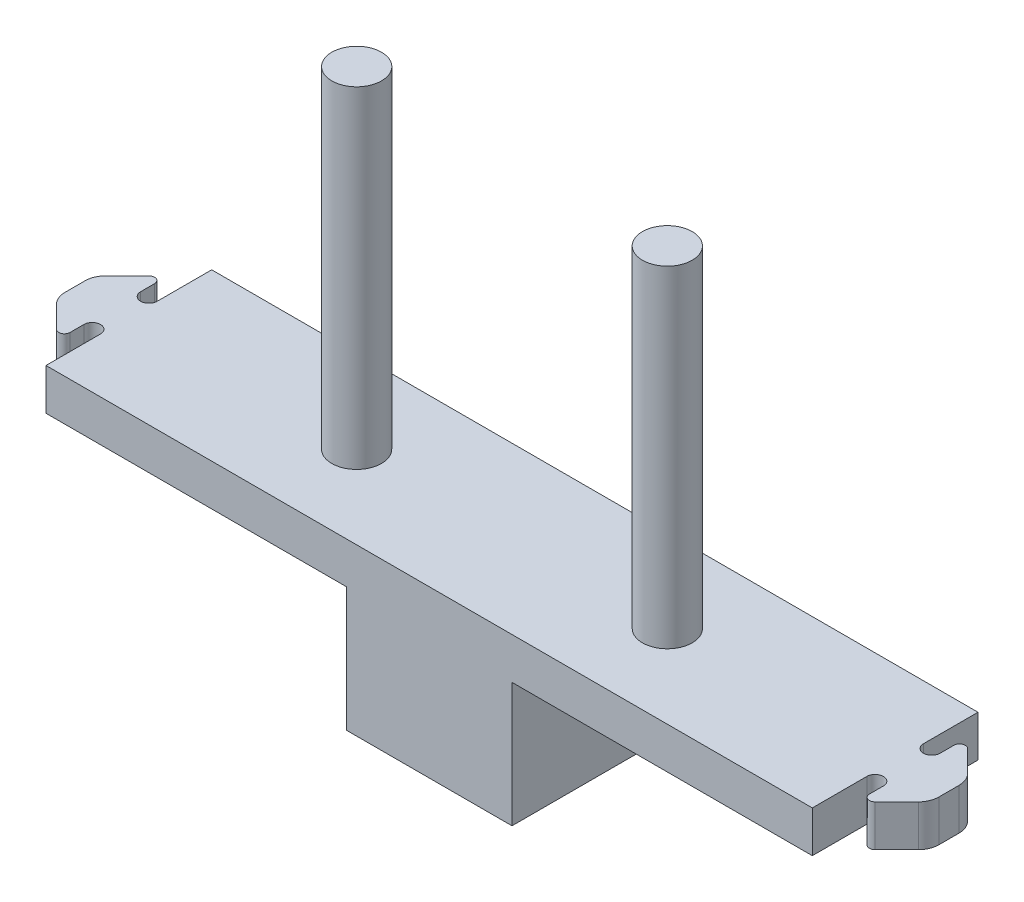
SolidWorks part; units mm, degrees
ref_plane "Front Plane" through (0, 0, 0) normal (0, 0, 1) x (1, 0, 0)
ref_plane "Top Plane" through (0, 0, 0) normal (0, 1, 0) x (1, 0, 0)
ref_plane "Right Plane" through (0, 0, 0) normal (1, 0, 0) x (0, 0, -1)
sketch "Sketch1" plane through (0, 0, 0) normal (0, 1, 0) x (1, 0, 0)
  line L0 (12.1572, -15.7678) -> (7.8138, -15.7678)
  line L1 (0, 0) -> (-117.475, 0)
  line L2 (0, 0) -> (0, -25.4)
  line L3 (0, -25.4) -> (-117.475, -25.4)
  line L4 (-117.475, 0) -> (-117.475, -25.4)
  line L13 (7.8138, -13.2278) -> (5.6802, -13.2278)
  line L14 (5.0695, -11.7535) -> (8.3922, -8.4308)
  line L15 (10.6437, -7.5166) -> (12.1572, -7.5166)
  line L16 (12.1572, -7.5166) -> (12.1572, -15.7678)
  arc A0 (7.8138, -15.7678) -> (7.8138, -13.2278) centre (7.8138, -14.4978) ccw
  arc A1 (5.6802, -13.2278) -> (5.0695, -11.7535) centre (5.6802, -12.3642) cw
  arc A2 (8.3922, -8.4308) -> (10.6437, -7.5166) centre (10.6216, -10.6915) cw
  point P18 (11.4004, -7.5166)
  dimension "D5" = 6.477
  dimension "D7" = 1.27
  dimension "D8" = 0.8636
  dimension "D9" = 3.175
  dimension "D1" = 117.475
  dimension "D2" = 25.4
  dimension "D3" = 4.3434
  dimension "D4" = 8.2512
  dimension "D6" = 45
  dimension "D10" = 2.54
  dimension "D11" = 3.4036
  dimension "D12" = 5.0763
  dimension "D13" = 1.5356
  dimension "D14" = 4.3434
  dimension "D15" = 4.0143
extrude "Boss-Extrude1" add sketch "Sketch1" along normal blind 6.35
sketch "Sketch3" plane through (0, 6.35, 0) normal (0, 1, 0) x (1, 0, 0)
  line L0 (0, 0) -> (-117.475, 0) construction
  line L1 (-114.3, 0) -> (-3.175, 0)
  line L2 (-114.3, 0) -> (-114.3, -25.4)
  line L3 (-114.3, -25.4) -> (-3.175, -25.4)
  line L4 (-3.175, 0) -> (-3.175, -25.4)
  line L5 (0, -25.4) -> (-117.475, -25.4) construction
  line L6 (0, -25.4) -> (-117.475, -25.4) construction
  circle A0 centre (-34.925, -12.7) radius 3.81
  circle A1 centre (-82.55, -12.7) radius 3.81
  point P8 (-58.7375, 0)
  point P11 (-58.7375, -25.4)
  dimension "D3" = 12.7
  dimension "D7" = 7.62
  dimension "D8" = 7.62
  dimension "D1" = 111.125
  dimension "D2" = 0
  dimension "D4" = 31.75
  dimension "D5" = 12.7
  dimension "D6" = 31.75
extrude "Boss-Extrude2" add sketch "Sketch3" along normal blind 50.8 contours A0 | A1
sketch "Sketch4" plane through (0, 6.35, 0) normal (0, 1, 0) x (1, 0, 0)
  circle A0 centre (-82.55, -12.7) radius 12.7
  circle A1 centre (-34.925, -12.7) radius 12.7
extrude "Boss-Extrude3" [suppressed] add sketch "Sketch4" along normal blind 50.8
ref_plane "Plane1" through (-58.7375, 0, 0) normal (-1, 0, 0) x (0, 0, 1)
sketch "Sketch10" plane through (0, 6.35, 0) normal (0, 1, 0) x (1, 0, 0)
  line L5 (0, -12.7) -> (0, -8.3566)
  line L6 (2.54, -8.3566) -> (2.54, -6.223)
  line L7 (4.0143, -5.6123) -> (7.337, -8.935)
  line L8 (8.2512, -11.1865) -> (8.2512, -12.7)
  line L9 (8.2512, -12.7) -> (0, -12.7)
  line L10 (-58.7375, 3.4925) -> (-58.7375, -3.4925) construction
  line L11 (0, 0) -> (0, -25.4) construction
  line L12 (-117.475, -12.7) -> (-117.475, -8.3566)
  line L13 (-120.015, -8.3566) -> (-120.015, -6.223)
  line L14 (-121.4893, -5.6123) -> (-124.812, -8.935)
  line L15 (-125.7262, -11.1865) -> (-125.7262, -12.7)
  line L16 (-125.7262, -12.7) -> (-117.475, -12.7)
  arc A3 (0, -8.3566) -> (2.54, -8.3566) centre (1.27, -8.3566) ccw
  arc A4 (2.54, -6.223) -> (4.0143, -5.6123) centre (3.4036, -6.223) cw
  arc A5 (7.337, -8.935) -> (8.2512, -11.1865) centre (5.0763, -11.1644) cw
  arc A6 (-117.475, -8.3566) -> (-120.015, -8.3566) centre (-118.745, -8.3566) cw
  arc A7 (-120.015, -6.223) -> (-121.4893, -5.6123) centre (-120.8786, -6.223) ccw
  arc A8 (-124.812, -8.935) -> (-125.7262, -11.1865) centre (-122.5513, -11.1644) ccw
  point P2 (0, -12.7)
extrude "Boss-Extrude7" add sketch "Sketch10" against normal blind 6.35
mirror "Mirror1" about plane through (8.2512, 0, 12.7) normal (0, 0, 1) of "Boss-Extrude7"
sketch "Sketch12" plane through (0, 0, 0) normal (0, -1, 0) x (-1, 0, 0)
  line L0 (0, -25.4) -> (117.475, -25.4) construction
  line L1 (71.4375, -25.4) -> (46.0375, -25.4)
  line L2 (71.4375, -25.4) -> (71.4375, 0)
  line L3 (71.4375, 0) -> (46.0375, 0)
  line L4 (46.0375, -25.4) -> (46.0375, 0)
  line L5 (0, 0) -> (117.475, 0) construction
  point P8 (58.7375, 0)
  point P9 (58.7375, 0)
  dimension "D1" = 25.4
extrude "Boss-Extrude8" add sketch "Sketch12" along normal blind 19.05 contours L2 L1 L4 L3
